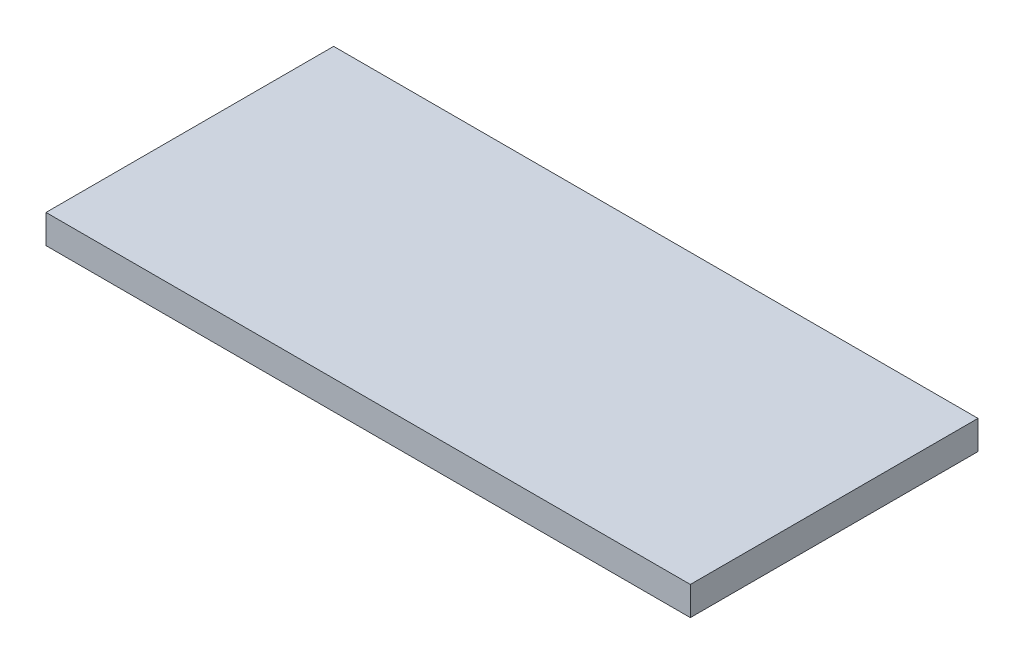
SolidWorks part; units mm, degrees
material "AISI 1020 Steel, Cold Rolled"
ref_plane "Front Plane" through (0, 0, 0) normal (0, 0, 1) x (1, 0, 0)
ref_plane "Top Plane" through (0, 0, 0) normal (0, 1, 0) x (1, 0, 0)
ref_plane "Right Plane" through (0, 0, 0) normal (1, 0, 0) x (0, 0, -1)
sketch "Sketch1" plane through (0, 0, 0) normal (0, 1, 0) x (1, 0, 0)
  line L1 (17.78, -7.9375) -> (-17.78, -7.9375)
  line L2 (17.78, -7.9375) -> (17.78, 7.9375)
  line L3 (17.78, 7.9375) -> (-17.78, 7.9375)
  line L4 (-17.78, -7.9375) -> (-17.78, 7.9375)
  line L5 (17.78, -7.9375) -> (-17.78, 7.9375) construction
  line L6 (17.78, 7.9375) -> (-17.78, -7.9375) construction
  point P0 (0, 0)
  dimension "D1" = 35.56
  dimension "D2" = 15.875
extrude "Boss-Extrude1" add sketch "Sketch1" along normal blind 1.5875
